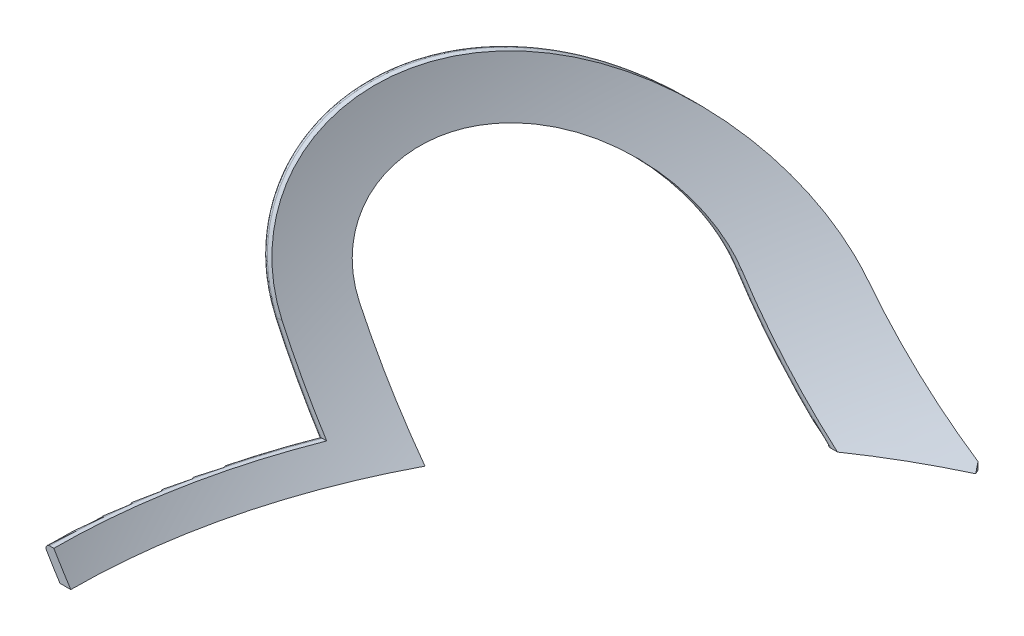
SolidWorks part; units mm, degrees
ref_plane "Front Plane" through (0, 0, 0) normal (0, 0, 1) x (1, 0, 0)
ref_plane "Top Plane" through (0, 0, 0) normal (0, 1, 0) x (1, 0, 0)
ref_plane "Right Plane" through (0, 0, 0) normal (1, 0, 0) x (0, 0, -1)
sketch "Sketch1" plane through (0, 0, 0) normal (0, 0, 1) x (1, 0, 0)
  line L0 (-194.945, -11.7951) -> (-198.7261, -11.7951)
  line L1 (-194.945, -11.7951) -> (-170.4726, -11.7951) construction
  line L2 (-232.4595, 83.4549) -> (-235.6816, 83.4549)
  line L3 (-182.6749, 64.4049) -> (-186.6337, 64.4049) construction
  line L4 (17.78, 127) -> (17.78, 273.6933) construction
  arc A0 (-232.4595, 83.4549) -> (-194.945, -11.7951) centre (17.78, 127) ccw
  arc A1 (-218.7832, 34.513) -> (-205.1291, 5.2316) centre (17.78, 127) ccw construction
  arc A2 (-235.6816, 83.4549) -> (-198.7261, -11.7951) centre (17.78, 127) ccw
  circle A3 centre (17.78, 127) radius 257.175 construction
  circle A4 centre (17.78, 127) radius 254 construction
  spline S0 degree 3 poles (-136.0395, 26.3049) (-137.4308, 28.4303) (-138.8968, 30.4598) (-141.9384, 34.3723) (-143.5146, 36.2548) (-145.9475, 38.9838) (-146.77, 39.8775) (-148.0201, 41.195) (-148.4396, 41.6304) (-149.2786, 42.4882) (-149.6987, 42.9113) (-151.8022, 44.9986) (-153.4944, 46.5794) (-156.8935, 49.576) (-158.6005, 50.9917) (-161.1718, 52.992) (-162.0307, 53.6381) (-163.7522, 54.888) (-164.6162, 55.4926) (-167.1836, 57.2202) (-168.8718, 58.2647) (-172.2032, 60.1352) (-173.8463, 60.9611) (-176.2776, 62.0222) (-177.0825, 62.3461) (-178.2812, 62.7843) (-178.6794, 62.9224) (-179.4729, 63.1821) (-179.8688, 63.3037) (-181.8271, 63.8651) (-183.3362, 64.1679) (-186.2363, 64.4543) (-187.6274, 64.4383) (-189.285, 64.1833) (-189.6126, 64.1203) (-190.2536, 63.9708) (-190.5677, 63.8843) (-191.4905, 63.5884) (-192.0798, 63.3429) (-193.205, 62.7496) (-193.7409, 62.4018) (-194.5019, 61.7967) (-194.7485, 61.581) (-195.2267, 61.1204) (-195.4587, 60.875) (-196.5672, 59.5853) (-197.3011, 58.3475) (-198.0131, 56.5156) (-198.1452, 56.1349) (-198.3877, 55.3433) (-198.498, 54.9324) (-198.7915, 53.6713) (-199.0865, 51.9041) (-199.1907, 49.9658) (-199.1956, 48.4463) (-199.1849, 47.9288) (-199.1386, 46.8713) (-199.1029, 46.3319) (-199.0551, 45.7893) knots 0 0 0 0 0.0625 0.0625 0.125 0.125 0.15625 0.15625 0.171875 0.171875 0.1875 0.1875 0.25 0.25 0.3125 0.3125 0.34375 0.34375 0.375 0.375 0.4375 0.4375 0.5 0.5 0.53125 0.53125 0.546875 0.546875 0.5625 0.5625 0.625 0.625 0.6875 0.6875 0.703125 0.703125 0.71875 0.71875 0.75 0.75 0.78125 0.78125 0.796875 0.796875 0.8125 0.8125 0.875 0.875 0.890625 0.890625 0.90625 0.90625 0.9375 0.96875 0.96875 0.984375 0.984375 1 1 1 1 construction
  point P13 (-186.7367, 64.4049)
  dimension "D2" = 19.05
  dimension "D1" = 3.175
revolve "Revolve1" add sketch "Sketch1" angle 130 mid plane about L4
sketch "Sketch2" plane through (0, 0, 0) normal (1, 0, 0) x (0, 0, -1)
  line L20 (99.06, 26.3049) -> (99.06, -49.8951)
  line L21 (175.26, -49.8951) -> (175.26, 26.3049)
  line L24 (-99.06, -49.8951) -> (-99.06, 26.3049)
  line L25 (-175.26, 26.3049) -> (-175.26, -49.8951)
  line L30 (80.01, 26.3049) -> (80.01, -49.8951)
  line L31 (194.31, -49.8951) -> (194.31, 26.3049)
  line L34 (0, -11.7951) -> (0, 83.4549)
  line L35 (80.01, -2.2701) -> (-99.06, -2.2701)
  line L36 (-196.2212, -11.7951) -> (196.2212, -11.7951)
  line L37 (229.7143, 83.4549) -> (-229.7143, 83.4549)
  line L38 (-196.2212, -11.7951) -> (196.2212, -11.7951)
  line L39 (229.7143, 83.4549) -> (-229.7143, 83.4549)
  arc A20 (175.26, 26.3049) -> (99.06, 26.3049) centre (137.16, 26.3049) ccw
  arc A21 (99.06, -49.8951) -> (175.26, -49.8951) centre (137.16, -49.8951) ccw
  arc A24 (-175.26, -49.8951) -> (-99.06, -49.8951) centre (-137.16, -49.8951) ccw
  arc A25 (-99.06, 26.3049) -> (-175.26, 26.3049) centre (-137.16, 26.3049) ccw
  arc A30 (80.01, -49.8951) -> (194.31, -49.8951) centre (137.16, -49.8951) ccw
  arc A31 (194.31, 26.3049) -> (80.01, 26.3049) centre (137.16, 26.3049) ccw
  ellipse E2 centre (0, 127) end of major axis (0, 384.175) minor radius 233.0797 (-229.7143, 83.4549) -> (-196.2212, -11.7951) ccw
  ellipse E3 centre (0, 127) end of major axis (0, 384.175) minor radius 233.0797 (196.2212, -11.7951) -> (229.7143, 83.4549) ccw
  ellipse E4 centre (0, 127) end of major axis (0, 384.175) minor radius 233.0797 (-229.7143, 83.4549) -> (-196.2212, -11.7951) ccw
  ellipse E5 centre (0, 127) end of major axis (0, 384.175) minor radius 233.0797 (196.2212, -11.7951) -> (229.7143, 83.4549) ccw
  dimension "D3" = 9.525
  dimension "D1" = 19.05
  dimension "D2" = 0
extrude "Cut-Extrude1" cut sketch "Sketch2" against normal through all contours L38 E5 L39 A31 L31 | A31 L39 L34 L35 L30 | L39 E4 L38 L25 A25 L24 L35 L34 | L24 L38 L34 L35 | L24 A25 L25 L38 | L21 A20 L20 L38
fillet "Fillet1" radius 1.27 7 edges at (-186.8216, 6.7325, -99.06) (-199.0058, 61.11, -121.6611) (-99.0624, 5.6309, -194.31) (-205.337, 80.5474, -119.1635) (-126.5453, 6.198, -175.26) (-197.7613, 11.764, -80.01) (-200.7889, -2.2701, -40.6924)
